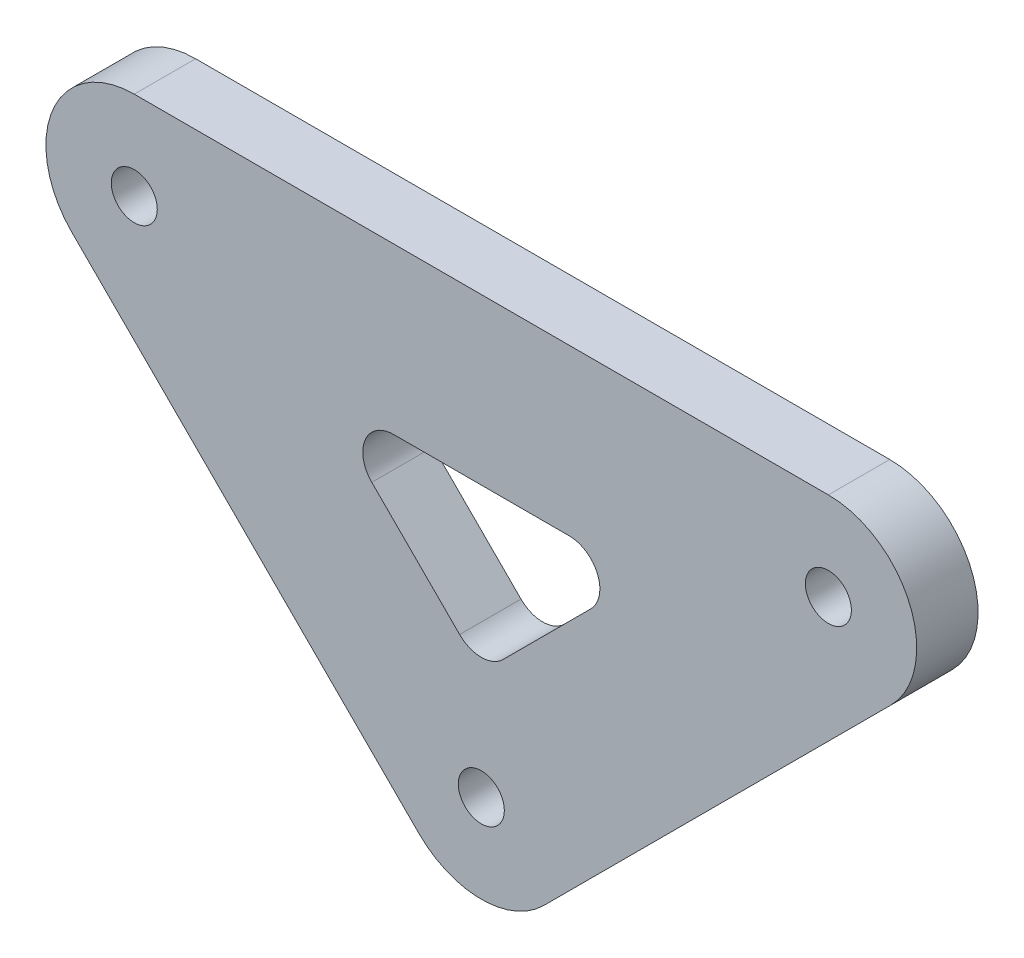
SolidWorks part; units mm, degrees
material "Acrílico (Impacto medio-alto)"
ref_plane "Piano frontale" through (0, 0, 0) normal (0, 0, 1) x (1, 0, 0)
ref_plane "Piano superiore" through (0, 0, 0) normal (0, 1, 0) x (1, 0, 0)
ref_plane "Piano destro" through (0, 0, 0) normal (1, 0, 0) x (0, 0, -1)
sketch "Schizzo1" plane through (0, 0, 0) normal (0, 0, 1) x (1, 0, 0)
  line L0 (0, -9.7873) -> (0, 53.0062) construction
  line L1 (-36.5346, 28.388) -> (-22.6274, 28.388) construction
  line L2 (22.6274, 28.388) -> (36.5346, 28.388) construction
  line L3 (36.5346, 28.388) -> (26.7007, 18.5541) construction
  line L4 (22.6274, 28.388) -> (-22.6274, 28.388)
  line L5 (4.0733, -4.0733) -> (26.7007, 18.5541)
  line L6 (5.7279, 17.6274) -> (-5.7279, 17.6274)
  line L7 (-7.1421, 14.2132) -> (-1.4142, 8.4853)
  line L8 (1.4142, 8.4853) -> (7.1421, 14.2132)
  line L9 (-26.7007, 18.5541) -> (-4.0733, -4.0733)
  line L10 (4.0733, -4.0733) -> (0, -8.1467) construction
  line L11 (0, -8.1467) -> (-4.0733, -4.0733) construction
  line L12 (-36.5346, 28.388) -> (-26.7007, 18.5541) construction
  line L13 (-22.6274, 22.6274) -> (0, 0) construction
  line L14 (0, 0) -> (22.6274, 22.6274) construction
  line L15 (22.6274, 22.6274) -> (-22.6274, 22.6274) construction
  circle A0 centre (0, 0) radius 1.5
  arc A1 (-4.0733, -4.0733) -> (4.0733, -4.0733) centre (0, 0) ccw
  circle A2 centre (22.6274, 22.6274) radius 1.5
  circle A3 centre (-22.6274, 22.6274) radius 1.5
  arc A4 (-26.7007, 18.5541) -> (-22.6274, 28.388) centre (-22.6274, 22.6274) cw
  arc A5 (22.6274, 28.388) -> (26.7007, 18.5541) centre (22.6274, 22.6274) cw
  arc A6 (-1.4142, 8.4853) -> (1.4142, 8.4853) centre (0, 9.8995) ccw
  arc A7 (5.7279, 17.6274) -> (7.1421, 14.2132) centre (5.7279, 15.6274) cw
  arc A8 (-5.7279, 17.6274) -> (-7.1421, 14.2132) centre (-5.7279, 15.6274) ccw
  point P13 (0, 7.0711)
  point P23 (10.5563, 17.6274)
  point P29 (-10.5563, 17.6274)
  dimension "D1" = 3
  dimension "D3" = 3
  dimension "D4" = 3
  dimension "D5" = 5
  dimension "D6" = 2
  dimension "D9" = 32
  dimension "D10" = 32
  dimension "D2" = 5
  dimension "D11" = 90
extrude "Estrusione-Estrusione1" add sketch "Schizzo1" along normal blind 4
